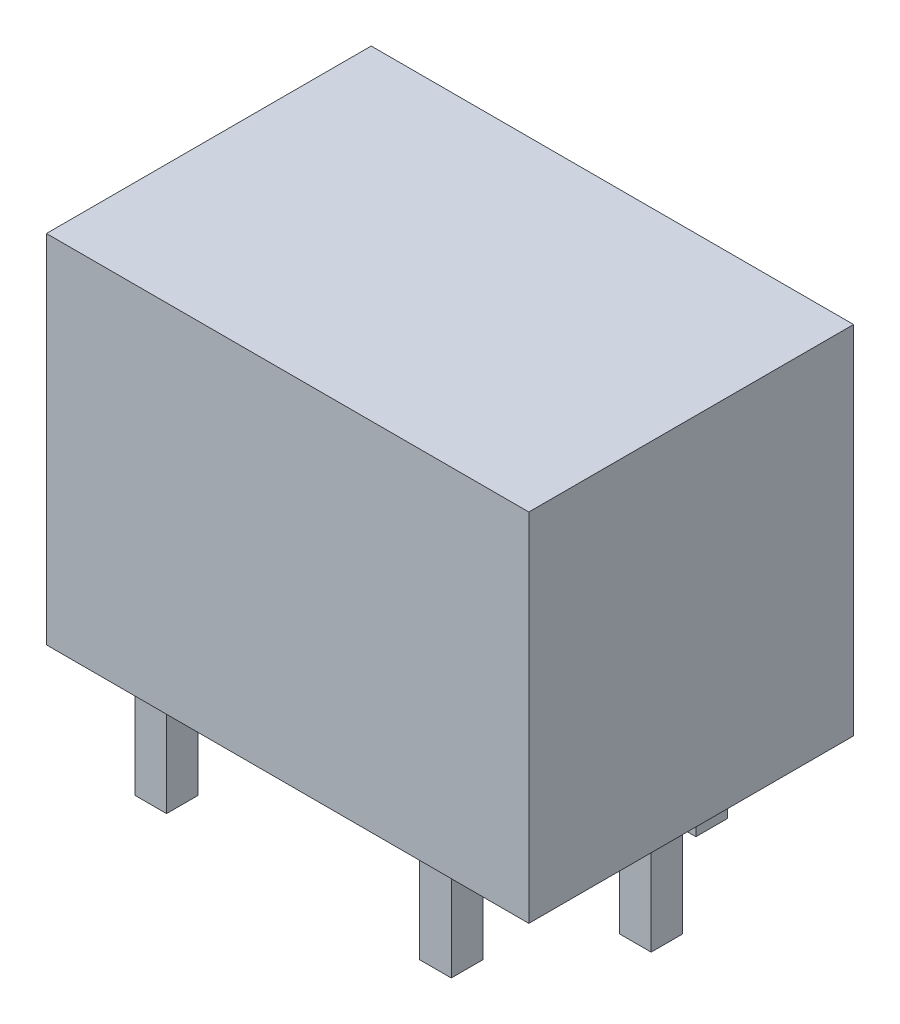
SolidWorks part; units mm, degrees
ref_plane "前视基准面" through (0, 0, 0) normal (0, 0, 1) x (1, 0, 0)
ref_plane "上视基准面" through (0, 0, 0) normal (0, 1, 0) x (1, 0, 0)
ref_plane "右视基准面" through (0, 0, 0) normal (1, 0, 0) x (0, 0, -1)
sketch "草图1" plane through (0, 0, 0) normal (0, 1, 0) x (1, 0, 0)
  line L0 (0, 41.7773) -> (0, -45.7415) construction
  line L1 (-7.65, 5.15) -> (7.65, 5.15)
  line L2 (-7.65, 5.15) -> (-7.65, -5.15)
  line L3 (-7.65, -5.15) -> (7.65, -5.15)
  line L4 (7.65, 5.15) -> (7.65, -5.15)
  line L5 (-48.486, 0) -> (58.5492, 0) construction
  dimension "D1" = 15.3
  dimension "D2" = 10.3
extrude "拉伸1" add sketch "草图1" along normal blind 11.3
sketch "草图2" plane through (0, 0, 0) normal (0, -1, 0) x (1, 0, 0)
  line L0 (9.9294, 0) -> (-10.2276, 0) construction
  line L1 (6.88, -0.5) -> (5.88, -0.5)
  line L2 (6.88, -0.5) -> (6.88, 0.5)
  line L3 (6.88, 0.5) -> (5.88, 0.5)
  line L4 (5.88, -0.5) -> (5.88, 0.5)
  line L5 (6.38, -1.6251) -> (6.38, 1.1288) construction
  line L6 (7.65, 5.15) -> (7.65, -5.15) construction
  line L7 (8.0786, 3.88) -> (-8.6507, 3.88) construction
  line L8 (4.42, 4.38) -> (3.42, 4.38)
  line L9 (4.42, 4.38) -> (4.42, 3.38)
  line L10 (4.42, 3.38) -> (3.42, 3.38)
  line L11 (3.42, 4.38) -> (3.42, 3.38)
  line L12 (-7.65, 5.15) -> (7.65, 5.15) construction
  line L13 (3.92, 4.8939) -> (3.92, 7.944) construction
  line L14 (-4.61, 4.38) -> (-5.61, 4.38)
  line L15 (-4.61, 4.38) -> (-4.61, 3.38)
  line L16 (-4.61, 3.38) -> (-5.61, 3.38)
  line L17 (-5.61, 4.38) -> (-5.61, 3.38)
  line L18 (-5.11, 7.128) -> (-5.11, 5.1977) construction
  line L19 (-7.65, -5.15) -> (-7.65, 5.15) construction
  line L20 (-5.61, -4.38) -> (-5.61, -3.38)
  line L21 (-4.61, -3.38) -> (-5.61, -3.38)
  line L22 (-4.61, -4.38) -> (-4.61, -3.38)
  line L23 (-4.61, -4.38) -> (-5.61, -4.38)
  line L24 (3.42, -4.38) -> (3.42, -3.38)
  line L25 (4.42, -3.38) -> (3.42, -3.38)
  line L26 (4.42, -4.38) -> (4.42, -3.38)
  line L27 (4.42, -4.38) -> (3.42, -4.38)
  dimension "D1" = 1
  dimension "D2" = 1
  dimension "D3" = 1.27
  dimension "D4" = 1
  dimension "D5" = 1
  dimension "D6" = 1.27
  dimension "D7" = 3.73
  dimension "D8" = 1
  dimension "D9" = 1
  dimension "D10" = 2.54
extrude "拉伸2" add sketch "草图2" along normal blind 3.5
